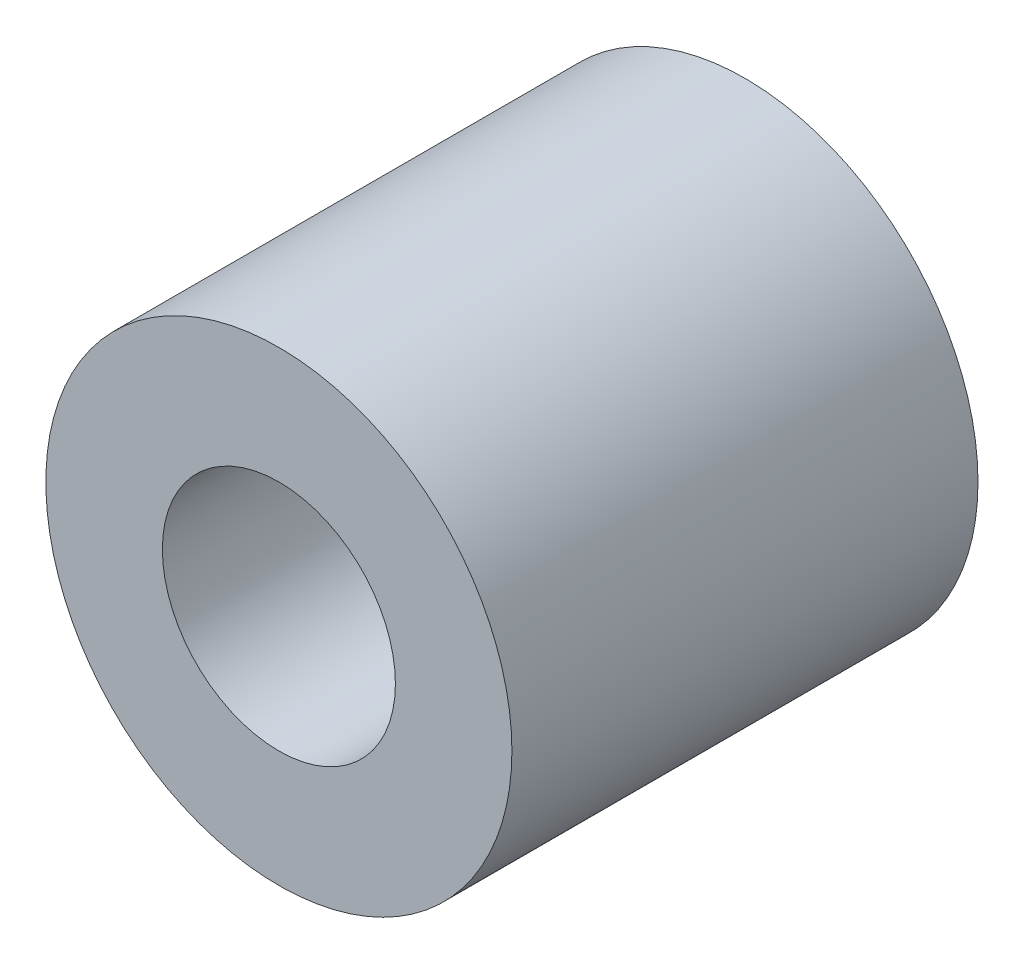
SolidWorks part; units mm, degrees
ref_plane "Front Plane" through (0, 0, 0) normal (0, 0, 1) x (1, 0, 0)
ref_plane "Top Plane" through (0, 0, 0) normal (0, 1, 0) x (1, 0, 0)
ref_plane "Right Plane" through (0, 0, 0) normal (1, 0, 0) x (0, 0, -1)
sketch "Sketch1" plane through (0, 0, 0) normal (0, 0, 1) x (1, 0, 0)
  circle A0 centre (0, 0) radius 6.35
  circle A1 centre (0, 0) radius 3.175
  dimension "D1" = 6.35
  dimension "D2" = 12.7
extrude "Boss-Extrude1" add sketch "Sketch1" along normal mid plane 12.7
